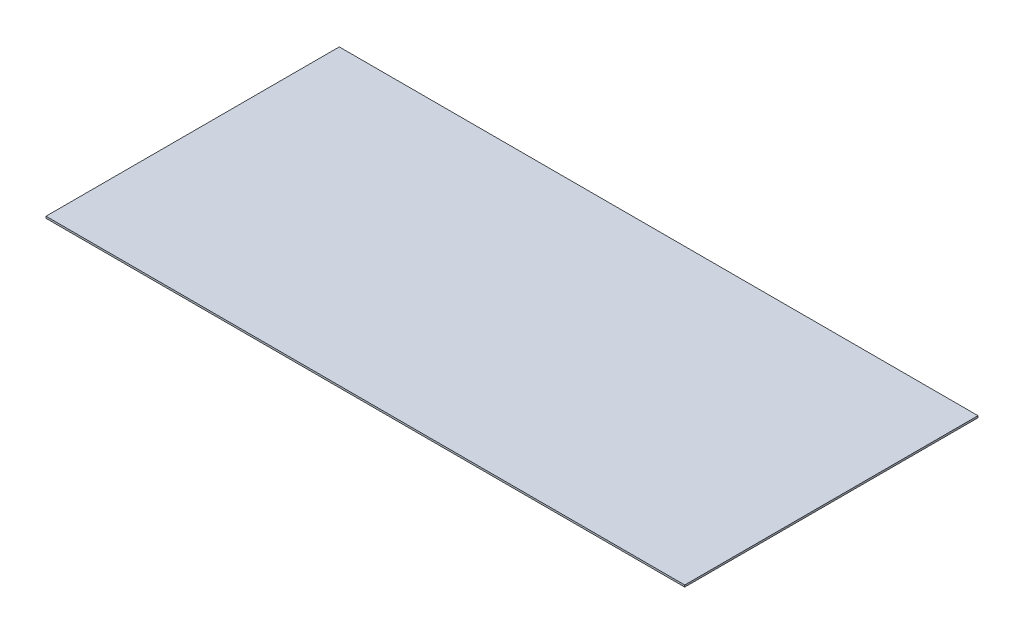
SolidWorks part; units mm, degrees
ref_plane "Front Plane" through (0, 0, 0) normal (0, 0, 1) x (1, 0, 0)
ref_plane "Top Plane" through (0, 0, 0) normal (0, 1, 0) x (1, 0, 0)
ref_plane "Right Plane" through (0, 0, 0) normal (1, 0, 0) x (0, 0, -1)
sketch "Sketch1" plane through (0, 0, 0) normal (0, 1, 0) x (1, 0, 0)
  line L1 (0, 0) -> (-1028, 0)
  line L2 (0, 0) -> (0, -472)
  line L3 (0, -472) -> (-1028, -472)
  line L4 (-1028, 0) -> (-1028, -472)
  dimension "D1" = 1028
  dimension "D2" = 472
extrude "Boss-Extrude1" add sketch "Sketch1" along normal blind 3
